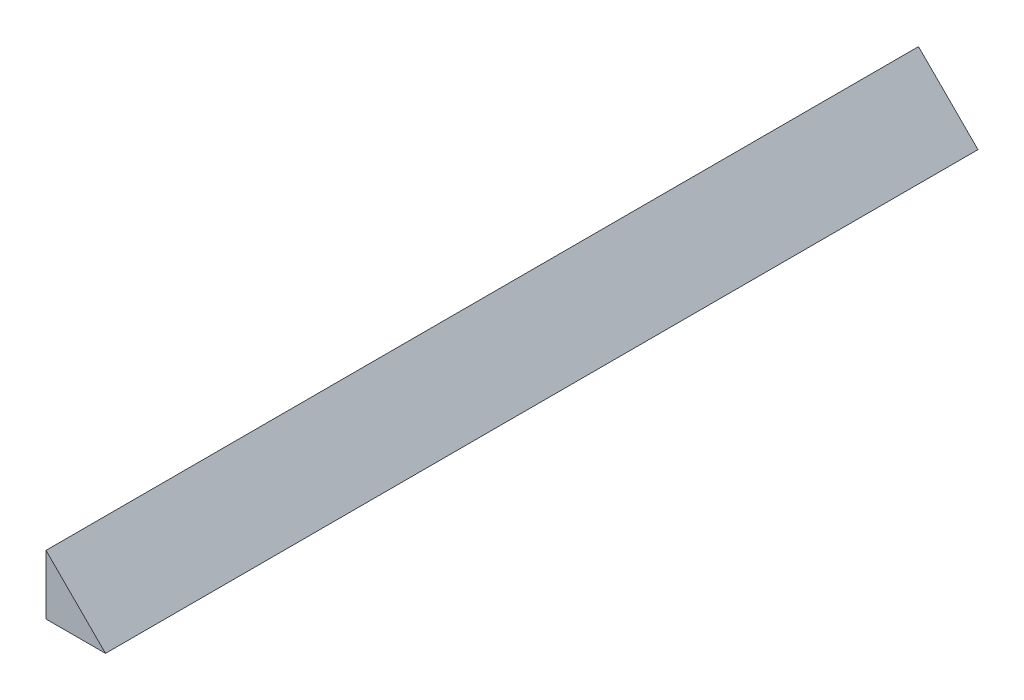
SolidWorks part; units mm, degrees
ref_plane "Front Plane" through (0, 0, 0) normal (0, 0, 1) x (1, 0, 0)
ref_plane "Top Plane" through (0, 0, 0) normal (0, 1, 0) x (1, 0, 0)
ref_plane "Right Plane" through (0, 0, 0) normal (1, 0, 0) x (0, 0, -1)
sketch "Sketch2" plane through (0, 0, 0) normal (0, 0, 1) x (1, 0, 0)
  line L0 (0, 0) -> (0, 15)
  line L1 (0, 15) -> (15, 0)
  line L2 (15, 0) -> (0, 0)
extrude "Boss-Extrude1" add sketch "Sketch2" along normal blind 220
